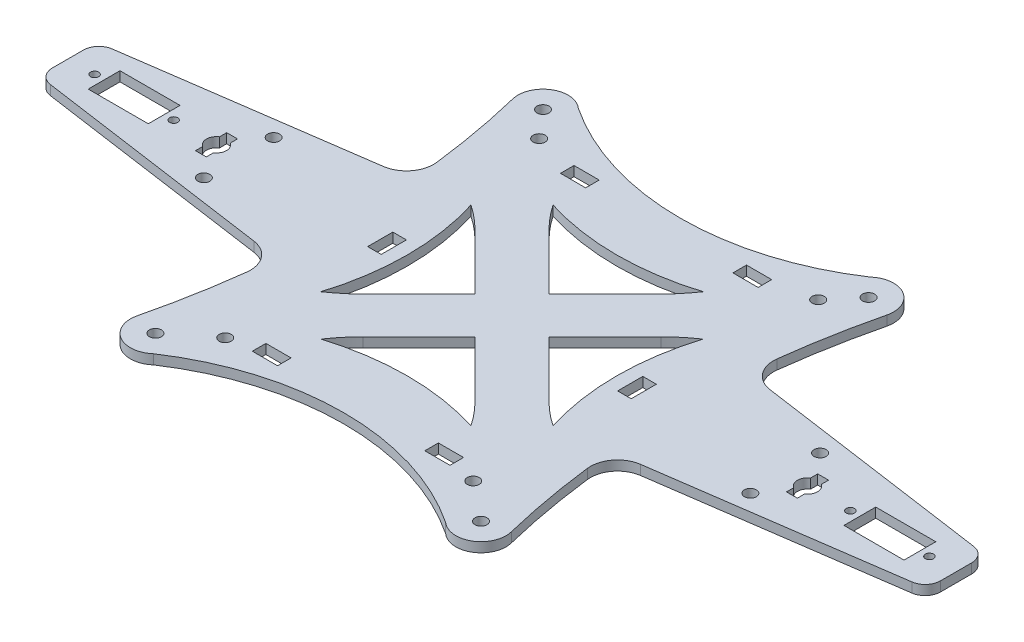
SolidWorks part; units mm, degrees
material "PPS"
ref_plane "前视基准面" through (0, 0, 0) normal (0, 0, 1) x (1, 0, 0)
ref_plane "上视基准面" through (0, 0, 0) normal (0, 1, 0) x (1, 0, 0)
ref_plane "右视基准面" through (0, 0, 0) normal (1, 0, 0) x (0, 0, -1)
sketch "草图1" plane through (0, 0, 0) normal (0, 1, 0) x (1, 0, 0)
  line L3 (-133.7177, 0) -> (146.3754, 0) construction
  line L56 (0, 96.0639) -> (0, -115.1457) construction
  line L65 (-25.5, 41.5) -> (-19, 41.5)
  line L66 (-34, 3.25) -> (-30.5, 3.25)
  line L70 (-34, 3.25) -> (-34, -3.25)
  line L76 (-34, -3.25) -> (-30.5, -3.25)
  line L80 (-30.5, 3.25) -> (-30.5, -3.25)
  line L81 (-25.5, -38) -> (-19, -38)
  line L82 (-25.5, -38) -> (-25.5, -41.5)
  line L83 (-25.5, -41.5) -> (-19, -41.5)
  line L84 (-19, -38) -> (-19, -41.5)
  line L85 (-19, 38) -> (-19, 41.5)
  line L86 (-25.5, 38) -> (-19, 38)
  line L142 (-25.5, 38) -> (-25.5, 41.5)
  line L143 (25.5, 38) -> (25.5, 41.5)
  line L144 (25.5, 38) -> (19, 38)
  line L145 (19, 38) -> (19, 41.5)
  line L146 (19, -38) -> (19, -41.5)
  line L147 (25.5, -41.5) -> (19, -41.5)
  line L148 (25.5, -38) -> (25.5, -41.5)
  line L149 (25.5, -38) -> (19, -38)
  line L150 (30.5, 3.25) -> (30.5, -3.25)
  line L151 (34, -3.25) -> (30.5, -3.25)
  line L152 (34, 3.25) -> (34, -3.25)
  line L153 (34, 3.25) -> (30.5, 3.25)
  line L154 (25.5, 41.5) -> (19, 41.5)
  line L155 (77.65, -2.1768) -> (77.65, -4.025)
  line L156 (74.85, 4.025) -> (77.65, 4.025)
  line L157 (74.85, 4.025) -> (74.85, 2.1768)
  line L158 (74.85, -4.025) -> (77.65, -4.025)
  line L159 (77.65, 4.025) -> (77.65, 2.1768)
  line L160 (74.85, -2.1768) -> (74.85, -4.025)
  line L161 (97.5, 7.6653) -> (97.5, -9.1503) construction
  line L162 (89.75, 4.1) -> (105.25, 4.1)
  line L163 (89.75, 4.1) -> (89.75, -4.1)
  line L164 (89.75, -4.1) -> (105.25, -4.1)
  line L165 (105.25, 4.1) -> (105.25, -4.1)
  line L166 (-97.5, 7.6653) -> (-97.5, -9.1503) construction
  line L167 (-105.25, 4.1) -> (-105.25, -4.1)
  line L168 (-89.75, -4.1) -> (-105.25, -4.1)
  line L169 (-89.75, 4.1) -> (-89.75, -4.1)
  line L170 (-89.75, 4.1) -> (-105.25, 4.1)
  line L171 (-74.85, -2.1768) -> (-74.85, -4.025)
  line L172 (-77.65, 4.025) -> (-77.65, 2.1768)
  line L173 (-74.85, -4.025) -> (-77.65, -4.025)
  line L174 (-74.85, 4.025) -> (-74.85, 2.1768)
  line L175 (-74.85, 4.025) -> (-77.65, 4.025)
  line L176 (-77.65, -2.1768) -> (-77.65, -4.025)
  line L177 (114.5911, 7.4683) -> (114.5911, -7.4683)
  line L178 (114.5911, 7.4683) -> (43.1936, 17.6463)
  line L179 (114.5911, -7.4683) -> (43.1936, -17.6463)
  line L180 (-114.5911, -7.4683) -> (-43.1936, -17.6463)
  line L181 (-114.5911, 7.4683) -> (-114.5911, -7.4683)
  line L182 (-114.5911, 7.4683) -> (-43.1936, 17.6463)
  line L183 (-23.978, 14.4296) -> (-9.5485, 0)
  line L184 (14.4296, 23.978) -> (0, 9.5485)
  line L185 (-23.978, -14.4296) -> (-9.5485, 0)
  line L186 (-14.4296, 23.978) -> (0, 9.5485)
  line L187 (23.978, -14.4296) -> (9.5485, 0)
  line L188 (23.978, 14.4296) -> (9.5485, 0)
  line L189 (-14.4296, -23.978) -> (0, -9.5485)
  line L190 (14.4296, -23.978) -> (0, -9.5485)
  circle A0 centre (-36, 43) radius 1.55
  circle A1 centre (-32, -42) radius 1.55
  circle A2 centre (32, -42) radius 1.55
  circle A3 centre (36, 43) radius 1.55
  circle A4 centre (42, 50) radius 1.55
  circle A5 centre (42, -50) radius 1.55
  circle A6 centre (-42, -50) radius 1.55
  circle A7 centre (-42, 50) radius 1.55
  arc A8 (74.85, 2.1768) -> (74.85, -2.1768) centre (76.25, 0) ccw
  arc A9 (77.65, -2.1768) -> (77.65, 2.1768) centre (76.25, 0) ccw
  circle A10 centre (107.7, 0) radius 1.05
  circle A11 centre (87.3, 0) radius 1.05
  circle A12 centre (-87.3, 0) radius 1.05
  circle A13 centre (-107.7, 0) radius 1.05
  arc A14 (-77.65, -2.1768) -> (-77.65, 2.1768) centre (-76.25, 0) cw
  arc A15 (-74.85, 2.1768) -> (-74.85, -2.1768) centre (-76.25, 0) cw
  arc A18 (-37.7098, 54.831) -> (37.7098, 54.831) centre (0, 111.5317) ccw
  arc A20 (48.2756, 48.4632) -> (43.1936, 17.6463) centre (246.1791, 0) ccw
  arc A21 (48.2756, 48.4632) -> (37.7098, 54.831) centre (42, 50) ccw
  arc A22 (-37.7098, -54.831) -> (37.7098, -54.831) centre (0, -111.5317) cw
  arc A23 (48.2756, -48.4632) -> (43.1936, -17.6463) centre (246.1791, 0) cw
  arc A24 (48.2756, -48.4632) -> (37.7098, -54.831) centre (42, -50) cw
  arc A26 (-48.2756, -48.4632) -> (-37.7098, -54.831) centre (-42, -50) ccw
  arc A27 (-48.2756, -48.4632) -> (-43.1936, -17.6463) centre (-246.1791, 0) ccw
  arc A28 (-48.2756, 48.4632) -> (-37.7098, 54.831) centre (-42, 50) cw
  arc A30 (-48.2756, 48.4632) -> (-43.1936, 17.6463) centre (-246.1791, 0) cw
  arc A31 (-23.978, 14.4296) -> (-29.9602, 19.3706) centre (-52.8883, -14.4807) ccw
  arc A32 (-23.978, -14.4296) -> (-29.9602, -19.3706) centre (-52.8883, 14.4807) cw
  arc A33 (-29.9602, -19.3706) -> (-29.9602, 19.3706) centre (-91.9966, 0) ccw
  arc A34 (-14.4296, 23.978) -> (-19.3706, 29.9602) centre (14.4807, 52.8883) cw
  arc A35 (-19.3706, 29.9602) -> (19.3706, 29.9602) centre (0, 91.9966) ccw
  arc A36 (14.4296, 23.978) -> (19.3706, 29.9602) centre (-14.4807, 52.8883) ccw
  arc A37 (23.978, 14.4296) -> (29.9602, 19.3706) centre (52.8883, -14.4807) cw
  arc A38 (29.9602, 19.3706) -> (29.9602, -19.3706) centre (91.9966, 0) ccw
  arc A39 (23.978, -14.4296) -> (29.9602, -19.3706) centre (52.8883, 14.4807) ccw
  arc A40 (14.4296, -23.978) -> (19.3706, -29.9602) centre (-14.4807, -52.8883) cw
  arc A41 (19.3706, -29.9602) -> (-19.3706, -29.9602) centre (0, -91.9966) ccw
  arc A42 (-14.4296, -23.978) -> (-19.3706, -29.9602) centre (14.4807, -52.8883) ccw
  circle A43 centre (70.5, 9) radius 1.55
  circle A44 centre (70.5, -9) radius 1.55
  circle A45 centre (-70.5, -9) radius 1.55
  circle A46 centre (-70.5, 9) radius 1.55
  point P118 (0, 0)
  dimension "D5" = 38
  dimension "D18" = 8.2
  dimension "D6" = 3.1
  dimension "D11" = 50
  dimension "D15" = 74.85
  dimension "D16" = 2.1
  dimension "D17" = 15.5
  dimension "D21" = 3.1
  dimension "D1" = 6.5
  dimension "D2" = 3.5
  dimension "D3" = 30.5
  dimension "D4" = 19
  dimension "D7" = 32
  dimension "D8" = 42
  dimension "D9" = 43
  dimension "D10" = 36
  dimension "D12" = 42
  dimension "D13" = 2.8
  dimension "D14" = 4
  dimension "D19" = 2.45
  dimension "D20" = 97.5
  dimension "D22" = 9
  dimension "D23" = 70.5
extrude "凸台-拉伸1" add sketch "草图1" along normal blind 2.5
fillet "圆角1" radius 4 4 edges at (114.5911, 1.25, -7.4683) (114.5911, 1.25, 7.4683) (-114.5911, 1.25, -7.4683) (-114.5911, 1.25, 7.4683)
fillet "圆角2" radius 7 4 edges at (-43.1936, 1.25, -17.6463) (43.1936, 1.25, -17.6463) (43.1936, 1.25, 17.6463) (-43.1936, 1.25, 17.6463)
